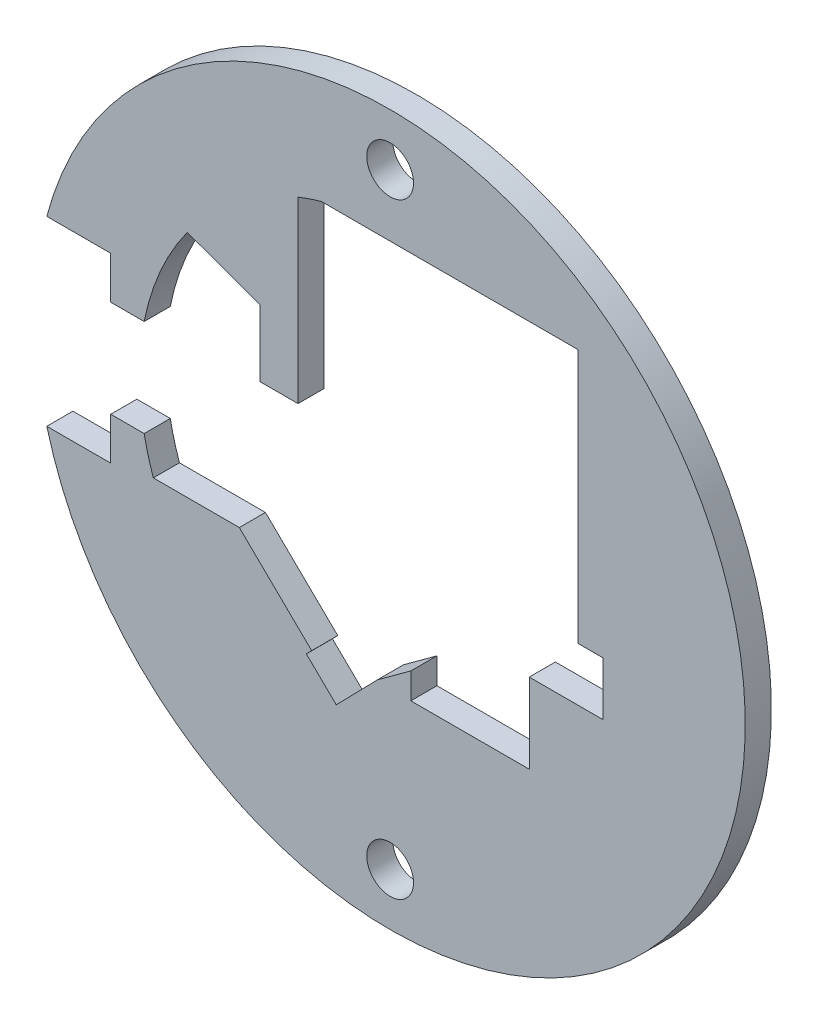
SolidWorks part; units mm, degrees
ref_plane "Front Plane" through (0, 0, 0) normal (0, 0, 1) x (1, 0, 0)
ref_plane "Top Plane" through (0, 0, 0) normal (0, 1, 0) x (1, 0, 0)
ref_plane "Right Plane" through (0, 0, 0) normal (1, 0, 0) x (0, 0, -1)
sketch "Sketch1" plane through (0, 0, 0) normal (0, 0, 1) x (1, 0, 0)
  line L1 (-14.9521, -2.9485) -> (-16.9841, -2.9485)
  line L2 (-16.9841, 2.9485) -> (-16.9841, 5.5245)
  line L3 (-14.9521, 2.9485) -> (-16.9841, 2.9485)
  line L4 (-16.9841, 5.5245) -> (-21.1739, 5.5245)
  line L5 (-16.9841, -2.9485) -> (-16.9841, -5.5245)
  line L6 (-16.9841, -5.5245) -> (-20.8712, -5.5245)
  line L7 (-15.24, 0) -> (-21.59, 0) construction
  line B0 (-15.24, 18.2372) -> (15.24, 18.2372)
  line B1 (11.43, 14.6558) -> (11.43, -0.8128)
  line B2 (0, 18.2372) -> (0, 0) construction
  line B3 (-5.6007, 14.1736) -> (-5.6007, -0.8128)
  line B4 (11.43, 14.6558) -> (-4.1791, 14.6558)
  line B5 (-5.6007, -0.8128) -> (11.43, -0.8128)
  line B6 (8.4582, -4.064) -> (12.9413, -4.064)
  line B7 (11.43, -0.8128) -> (12.9413, -0.8128)
  line B8 (12.9413, -0.8128) -> (12.9413, -4.064)
  line B9 (8.4582, -7.3406) -> (1.2573, -7.3406)
  line B10 (8.4582, -4.064) -> (8.4582, -7.3406)
  line B11 (-4.3942, -0.8128) -> (-4.3942, -4.064)
  line B12 (-4.3942, -4.064) -> (1.2573, -4.064)
  line B13 (1.2573, -4.064) -> (1.2573, -7.3406)
  line B14 (-0.7747, -8.8265) -> (-3.2737, -11.3919)
  line B15 (-0.7747, -8.8265) -> (-2.5941, -7.0541)
  line B16 (-2.5941, -7.0541) -> (-2.9176, -7.3862)
  line B17 (-2.9176, -7.3862) -> (-8.5123, -1.9362)
  line B18 (-8.5123, -1.9362) -> (-10.3645, -3.8375)
  line B19 (-10.3645, -3.8375) -> (-4.7697, -9.2875)
  line B20 (-4.7697, -9.2875) -> (-5.0932, -9.6195)
  line B21 (-5.0932, -9.6195) -> (-3.2737, -11.3919)
  line B22 (-12.3326, 18.2372) -> (-12.3326, 8.9535)
  line B23 (-7.9248, 18.2372) -> (-7.9248, 7.366) construction
  line B24 (-12.3326, 8.9535) -> (-7.9248, 7.366)
  line B25 (-5.6007, 3.302) -> (-7.9248, 3.302)
  line B26 (-7.9248, 3.302) -> (-7.9248, 7.366)
  line B27 (-14.3951, -5.0038) -> (-9.1672, -5.0038)
  line B28 (-0.7747, -8.8265) -> (1.2573, -7.3406)
  arc B29 (-3.302, 14.878) -> (3.302, 14.878) centre (0, 0) ccw
  circle B30 centre (0, -18.415) radius 1.4224
  circle B31 centre (0, 18.415) radius 1.4224
  circle B32 centre (0, 0) radius 21.59
  line B33 (1.2573, -8.9154) -> (8.4582, -8.9154)
  line B34 (1.2573, -7.3406) -> (1.2573, -8.9154)
  line B35 (8.4582, -7.3406) -> (8.4582, -8.9154)
  dimension "D1" = 2.032
  dimension "D2" = 11.049
sketch_block_instance "Block1-1"
sketch_block "Block1" parameters "D1"=3.81, "D2"=30.48, "D3"=3.5814, "D4"=9.6393, "D5"=19.05, "D6"=22.3012, "D7"=1.5113, "D8"=4.4831, "D9"=6.5278, "D10"=7.2009, "D11"=5.6515, "D12"=27.0637, "D13"=29.6291, "D14"=3.5814, "D15"=14.4653, "D16"=2.54, "D17"=2.6543, "D18"=10.3505, "D19"=9.2837, "D20"=10.8712, "D21"=7.3152, "D22"=14.9352, "D23"=23.241
extrude "Boss-Extrude1" add sketch "Sketch1" along normal blind 1.5875
